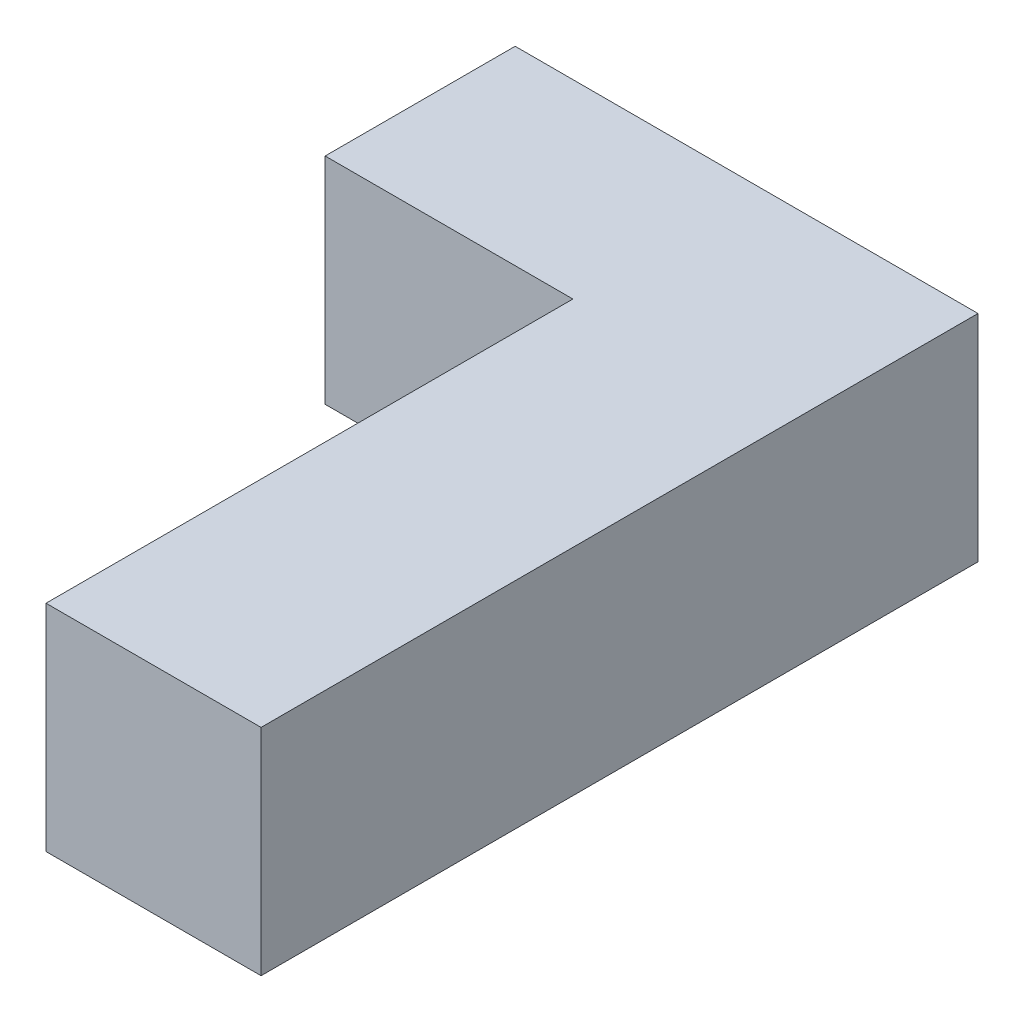
SolidWorks part; units mm, degrees
ref_plane "Front Plane" through (0, 0, 0) normal (0, 0, 1) x (1, 0, 0)
ref_plane "Top Plane" through (0, 0, 0) normal (0, 1, 0) x (1, 0, 0)
ref_plane "Right Plane" through (0, 0, 0) normal (1, 0, 0) x (0, 0, -1)
sketch "Sketch1" plane through (0, 0, 0) normal (0, 1, 0) x (1, 0, 0)
  line L1 (0, 0) -> (50, 0)
  line L2 (0, 0) -> (0, 50)
  line L3 (0, 50) -> (50, 50)
  line L4 (50, 0) -> (50, 50)
  dimension "D1" = 50
  dimension "D2" = 50
extrude "Boss-Extrude1" add sketch "Sketch1" along normal blind 15
sketch "Sketch2" plane through (0, 15, 0) normal (0, 1, 0) x (1, 0, 0)
  line L0 (50, 0) -> (50, 50) construction
  line L1 (17.7208, 51.7465) -> (17.7208, 36.7465)
  line L2 (17.7208, 36.7465) -> (35, 36.7465)
  line L3 (35, 36.7465) -> (35, -6.5766)
  line L4 (35, -6.5766) -> (-8.6829, -6.5766)
  line L5 (-8.6829, -6.5766) -> (-8.6829, 51.7465)
  line L6 (-8.6829, 51.7465) -> (17.7208, 51.7465)
  dimension "D1" = 15
  dimension "D2" = 15
extrude "Cut-Extrude1" cut sketch "Sketch2" against normal through all
